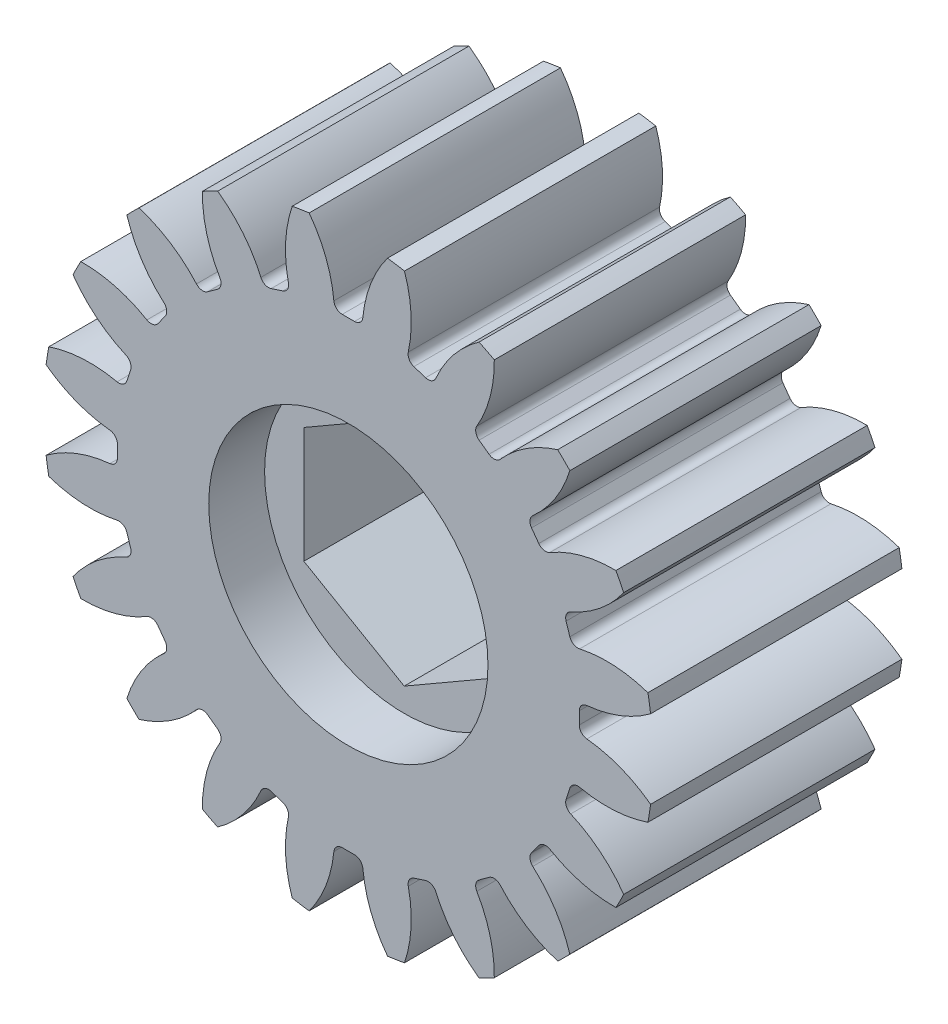
SolidWorks part; units mm, degrees
ref_plane "Ebene vorne" through (0, 0, 0) normal (0, 0, 1) x (1, 0, 0)
ref_plane "Ebene oben" through (0, 0, 0) normal (0, 1, 0) x (1, 0, 0)
ref_plane "Ebene rechts" through (0, 0, 0) normal (1, 0, 0) x (0, 0, -1)
sketch "Skizze1" plane through (0, 0, 0) normal (0, 0, 1) x (1, 0, 0)
  circle A0 centre (0, 0) radius 10.915
  dimension "D1" = 21.83
extrude "Aufsatz-Linear austragen1" add sketch "Skizze1" along normal mid plane 9
sketch "Skizze4" plane through (0, 0, 4.5) normal (0, 0, 1) x (1, 0, 0)
  circle A0 centre (0, 0) radius 2.5
  circle A1 centre (0, 0) radius 5
  dimension "D1" = 10
  dimension "D2" = 5
extrude "Schnitt-Linear austragen2" cut sketch "Skizze4" against normal blind 2
sketch "Skizze6" plane through (0, 0, 4.5) normal (0, 0, 1) x (1, 0, 0)
  line L0 (0, 0) -> (0, 10.915) construction
  line L1 (-0.2199, 8.27) -> (0.2199, 8.27)
  circle A0 centre (0, 0) radius 10.915 construction
  arc A1 (0.5184, 8.5407) -> (2.08, 11.55) centre (5.0567, 8.0956) cw
  arc A2 (-0.5184, 8.5407) -> (-2.08, 11.55) centre (-5.0567, 8.0956) ccw
  arc A3 (-2.08, 11.55) -> (2.08, 11.55) centre (0, -6.3294) cw
  arc A4 (0.2199, 8.27) -> (0.5184, 8.5407) centre (0.2199, 8.57) ccw
  arc A5 (-0.5184, 8.5407) -> (-0.2199, 8.27) centre (-0.2199, 8.57) ccw
  point P13 (0, 8.27)
  point P16 (0.5, 8.27)
  point P19 (-0.5, 8.27)
  dimension "D5" = 4.56
  dimension "D6" = 18
  dimension "D7" = 0.3
  dimension "D1" = 0.5
  dimension "D2" = 8.27
  dimension "D3" = 1.58
  dimension "D4" = 3.28
extrude "Schnitt-Linear austragen3" cut sketch "Skizze6" against normal through all
pattern_circular "Kreismuster1" count 20 over 360 about axis through (0, 0, 0) along (0, 0, 1) of "Schnitt-Linear austragen3"
sketch "Skizze8" plane through (0, 0, -4.5) normal (0, 0, -1) x (-1, 0, 0)
  circle A0 centre (0, 0) radius 6
extrude "Aufsatz-Linear austragen2" add sketch "Skizze8" along normal blind 1 contours A0
sketch "Skizze7" plane through (0, 0, 4.5) normal (0, 0, 1) x (1, 0, 0)
  line L1 (0, 4.15) -> (-3.594, 2.075)
  line L2 (-3.594, 2.075) -> (-3.594, -2.075)
  line L3 (-3.594, -2.075) -> (0, -4.15)
  line L4 (0, -4.15) -> (3.594, -2.075)
  line L5 (3.594, -2.075) -> (3.594, 2.075)
  line L6 (3.594, 2.075) -> (0, 4.15)
  circle A0 centre (0, 0) radius 3.594 construction
  dimension "D1" = 8.3
extrude "Schnitt-Linear austragen4" cut sketch "Skizze7" against normal through all
